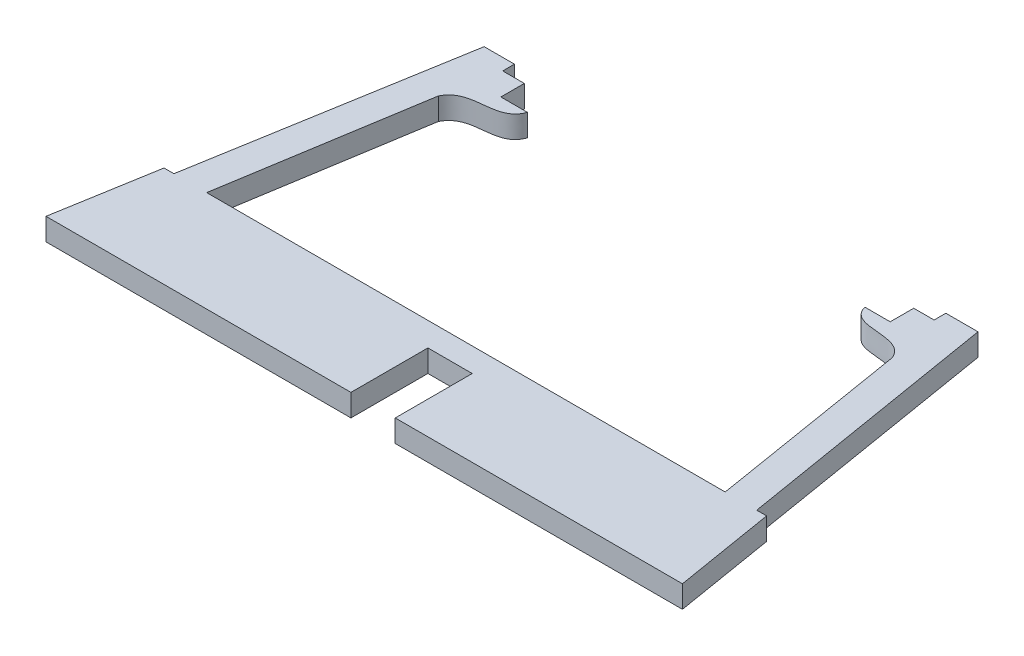
SolidWorks part; units mm, degrees
ref_plane "前视基准面" through (0, 0, 0) normal (0, 0, 1) x (1, 0, 0)
ref_plane "上视基准面" through (0, 0, 0) normal (0, 1, 0) x (1, 0, 0)
ref_plane "右视基准面" through (0, 0, 0) normal (1, 0, 0) x (0, 0, -1)
sketch "草图1" plane through (0, 0, 0) normal (0, 1, 0) x (1, 0, 0)
  line L0 (-19.4282, -5.7766) -> (-24.2276, -5.7766)
  line L1 (-24.2276, -5.7766) -> (-24.2276, -1.5353)
  line L2 (-24.2276, -1.5353) -> (-28.1341, -1.5353)
  line L3 (-28.1341, -1.5353) -> (-28.1341, 0.5854)
  line L4 (-28.1341, 0.5854) -> (-33.6032, 0.5854)
  line L5 (-33.6032, 0.5854) -> (-41.751, -47.2969)
  line L6 (-41.751, -47.2969) -> (-43.5368, -47.2969)
  line L7 (-43.5368, -47.2969) -> (-46.6362, -65.511)
  line L8 (-46.6362, -65.511) -> (8.433, -65.511)
  line L9 (8.433, -65.511) -> (8.433, -51.611)
  line L10 (8.433, -51.611) -> (16.433, -51.611)
  line L11 (16.433, -51.611) -> (16.433, -65.511)
  line L12 (16.433, -65.511) -> (68.3003, -65.511)
  line L13 (68.3003, -65.511) -> (65.2867, -47.2969)
  line L14 (65.2867, -47.2969) -> (63.5009, -47.2969)
  line L15 (63.5009, -47.2969) -> (55.5786, 0.5854)
  line L16 (55.5786, 0.5854) -> (49.7724, 0.5854)
  line L17 (49.7724, 0.5854) -> (49.7724, -1.5353)
  line L18 (49.7724, -1.5353) -> (46.0891, -1.5353)
  line L19 (46.0891, -1.5353) -> (46.0891, -5.7766)
  line L20 (46.0891, -5.7766) -> (41.5129, -5.7766)
  line L21 (-30.0315, -11.2457) -> (-35.8354, -47.2969)
  line L22 (-35.8354, -47.2969) -> (57.8086, -47.2969)
  line L23 (57.8086, -47.2969) -> (51.893, -11.2457)
  spline S0 degree 3 poles (-19.4282, -5.7766) (-21.0741, -10.3509) (-27.7783, -6.8198) (-30.0315, -11.2457) knots 0 0 0 0 1 1 1 1
  spline S1 degree 3 poles (41.5129, -5.7766) (42.6953, -10.4106) (50.0173, -6.5821) (51.893, -11.2457) knots 0 0 0 0 1 1 1 1
  dimension "D1" = 8
  dimension "D2" = 13.9
extrude "凸台-拉伸1" add sketch "草图1" along normal blind 4
